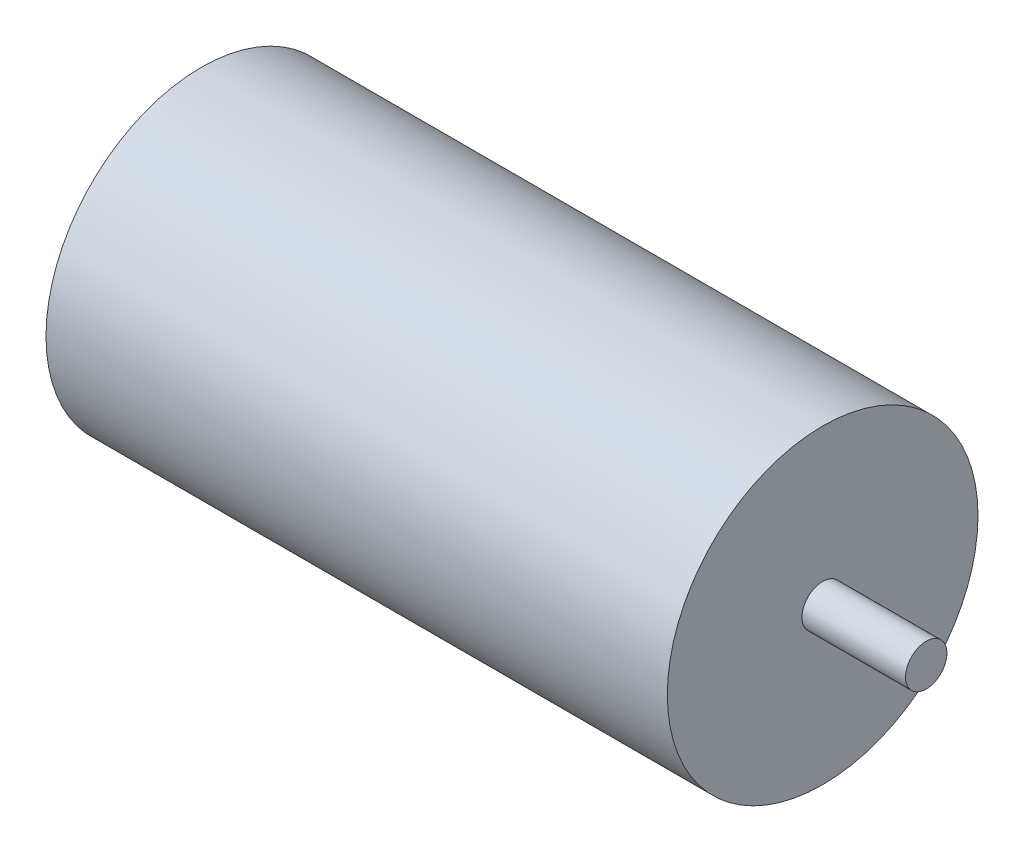
SolidWorks part; units mm, degrees
ref_plane "Front Plane" through (0, 0, 0) normal (0, 0, 1) x (1, 0, 0)
ref_plane "Top Plane" through (0, 0, 0) normal (0, 1, 0) x (1, 0, 0)
ref_plane "Right Plane" through (0, 0, 0) normal (1, 0, 0) x (0, 0, -1)
sketch "Sketch1" plane through (0, 0, 0) normal (1, 0, 0) x (0, 0, -1)
  circle A0 centre (0, 0) radius 30
  dimension "D1" = 60
extrude "Boss-Extrude1" add sketch "Sketch1" along normal blind 120
sketch "Sketch2" plane through (120, 0, 0) normal (1, 0, 0) x (0, 0, -1)
  circle A0 centre (0, 0) radius 4
  dimension "D1" = 8
extrude "Boss-Extrude2" add sketch "Sketch2" along normal blind 20
equation "\"WheelDiameter\" = 150mm"
equation "\"WheelRadius\" = \"WheelDiameter\" / 2"
equation "\"DT_WheelWidth\" = 45mm"
equation "\"DT_Wheelbase\" = 300mm"
equation "\"DT_ShaftDiameter\" = 12mm"
equation "\"DT_FrontShaftLength\" = 180mm"
equation "\"DT_RearShaftLength\" = 200mm"
equation "\"DT_BearingWidth\" = 20mm"
equation "\"DT_BearingHousingWidth\" = 60mm"
equation "\"DT_BearingHousingHeight\" = 35mm"
equation "\"DT_ChainPitch\" = 9.525mm"
equation "\"DT_SprocketTeeth\" = 18"
equation "\"DT_SprocketPitchDiameter\" = 54.851mm"
equation "\"DT_SprocketOuterDiameter\" = 60mm"
equation "\"DT_SprocketThickness\" = 6mm"
equation "\"DT_SprocketHubDiameter\" = 25mm"
equation "\"DT_SprocketHubLength\" = 20mm"
equation "\"DT_CouplingDiameter\" = 30mm"
equation "\"DT_CouplingLength\" = 35mm"
equation "\"DT_MotorDiameter\" = 60mm"
equation "\"DT_MotorLength\" = 120mm"
equation "\"DT_MotorShaftDiameter\" = 8mm"
equation "\"DT_MotorShaftLength\" = 20mm"
